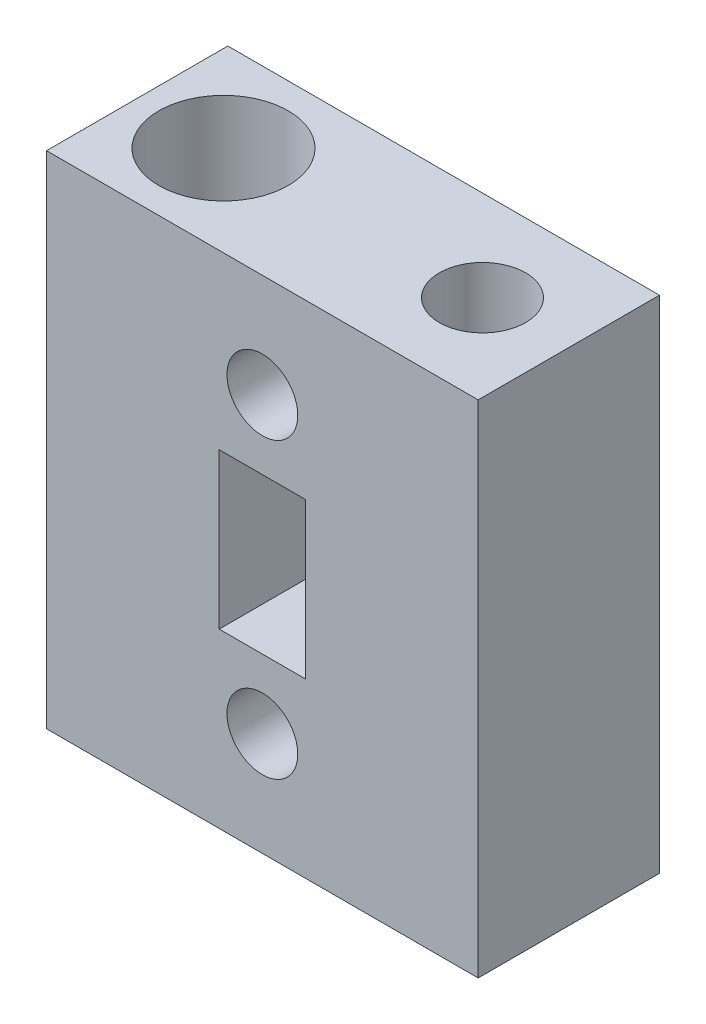
SolidWorks part; units mm, degrees
ref_plane "Front Plane" through (0, 0, 0) normal (0, 0, 1) x (1, 0, 0)
ref_plane "Top Plane" through (0, 0, 0) normal (0, 1, 0) x (1, 0, 0)
ref_plane "Right Plane" through (0, 0, 0) normal (1, 0, 0) x (0, 0, -1)
sketch "Sketch1" plane through (0, 0, 0) normal (0, 1, 0) x (1, 0, 0)
  line L1 (-25, 10.5) -> (25, 10.5)
  line L2 (-25, 10.5) -> (-25, -10.5)
  line L3 (-25, -10.5) -> (25, -10.5)
  line L4 (25, 10.5) -> (25, -10.5)
  line L5 (-25, 10.5) -> (25, -10.5) construction
  line L6 (-25, -10.5) -> (25, 10.5) construction
  point P0 (0, 0)
  dimension "D1" = 21
  dimension "D2" = 50
extrude "Boss-Extrude1" add sketch "Sketch1" along normal blind 58
sketch "Sketch3" plane through (0, 58, 0) normal (0, 1, 0) x (1, 0, 0)
  line L0 (-15, 0) -> (15, 0) construction
  circle A0 centre (-15, 0) radius 7.5
  dimension "D1" = 15
  dimension "D2" = 30
extrude "Cut-Extrude1" cut sketch "Sketch3" against normal blind 24 contours A0
sketch "Sketch4" plane through (0, 58, 0) normal (0, 1, 0) x (1, 0, 0)
  line L0 (-15, 0) -> (15, 0) construction
  circle A0 centre (15, 0) radius 5
  dimension "D1" = 10
extrude "Cut-Extrude2" cut sketch "Sketch4" against normal up to next
sketch "Sketch5" plane through (0, 0, 0) normal (0, -1, 0) x (1, 0, 0)
  circle A1 centre (-15, 0) radius 7.5
  circle A2 centre (-15, 0) radius 7.5
  dimension "D1" = 0
extrude "Cut-Extrude3" cut sketch "Sketch5" against normal blind 24
sketch "Sketch6" plane through (0, 0, 0) normal (0, -1, 0) x (1, 0, 0)
  circle A0 centre (-15, 0) radius 4.5
extrude "Cut-Extrude4" cut sketch "Sketch6" against normal up to next
sketch "Sketch7" plane through (0, 0, 10.5) normal (0, 0, 1) x (1, 0, 0)
  line L0 (0, 58) -> (0, 0) construction
  line L1 (-25, 58) -> (25, 58) construction
  line L2 (-25, 0) -> (25, 0) construction
  line L3 (-25, 29) -> (25, 29) construction
  line L4 (-25, 58) -> (-25, 0) construction
  line L5 (25, 58) -> (25, 0) construction
  circle A1 centre (0, 46) radius 4.1
  circle A2 centre (0, 12) radius 4.1
  point P24 (0, 12)
  dimension "D1" = 8.2
  dimension "D2" = 12
sketch "Sketch8" plane through (0, 0, 10.5) normal (0, 0, 1) x (1, 0, 0)
  line L0 (-25, 29) -> (25, 29) construction
  line L1 (-25, 58) -> (-25, 0) construction
  line L2 (25, 58) -> (25, 0) construction
  line L3 (0, 58) -> (0, 0) construction
  line L4 (-25, 58) -> (25, 58) construction
  line L6 (-5, 20) -> (5, 20)
  line L7 (-5, 20) -> (-5, 38)
  line L8 (-5, 38) -> (5, 38)
  line L9 (5, 20) -> (5, 38)
  line L10 (-5, 20) -> (5, 38) construction
  line L11 (-5, 38) -> (5, 20) construction
  point P11 (0, 29)
  dimension "D1" = 18
  dimension "D2" = 10
extrude "Cut-Extrude5" cut sketch "Sketch8" against normal up to next
sketch "Sketch10" plane through (0, 0, -10.5) normal (0, 0, -1) x (-1, 0, 0)
  line L0 (-25, 29) -> (25, 29) construction
  line L1 (-25, 58) -> (-25, 0) construction
  line L2 (25, 58) -> (25, 0) construction
  line L3 (0, 58) -> (0, 0) construction
  line L4 (-25, 58) -> (25, 58) construction
extrude "Cut-Extrude6" cut sketch "Sketch7" against normal blind 15
